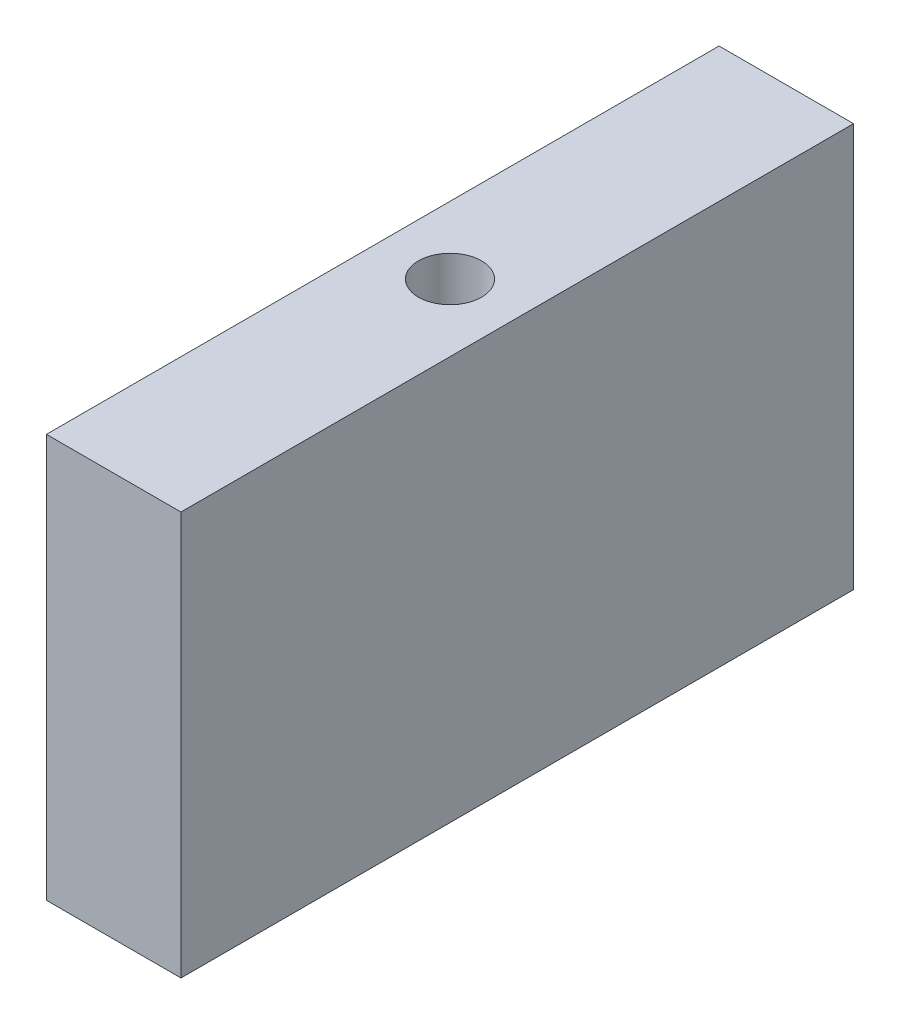
SolidWorks part; units mm, degrees
material "6061 Alloy"
ref_plane "Front Plane" through (0, 0, 0) normal (0, 0, 1) x (1, 0, 0)
ref_plane "Top Plane" through (0, 0, 0) normal (0, 1, 0) x (1, 0, 0)
ref_plane "Right Plane" through (0, 0, 0) normal (1, 0, 0) x (0, 0, -1)
sketch "Sketch1" plane through (0, 0, 0) normal (0, 1, 0) x (1, 0, 0)
  line L1 (-1.27, -6.35) -> (1.27, -6.35)
  line L2 (-1.27, -6.35) -> (-1.27, 6.35)
  line L3 (-1.27, 6.35) -> (1.27, 6.35)
  line L4 (1.27, -6.35) -> (1.27, 6.35)
  line L5 (-1.27, -6.35) -> (1.27, 6.35) construction
  line L6 (-1.27, 6.35) -> (1.27, -6.35) construction
  point P0 (0, 0)
  dimension "D1" = 2.54
  dimension "D2" = 12.7
extrude "Boss-Extrude1" add sketch "Sketch1" along normal blind 7.62
hole_wizard "#0-80 Tapped Hole1" positions "Sketch2" profile "Sketch3" tap size "#0-80" standard "ANSI Inch" end condition through all
sketch "Sketch2" plane through (0, 7.62, 0) normal (0, 1, 0) x (1, 0, 0)
  point P0 (0, 0)
sketch "Sketch3" plane through (0, 7.62, 0) normal (1, 0, 0) x (0, 0, 1)
  line L0 (0, 0) -> (0, 7.62)
  line L1 (0, 7.62) -> (0.5956, 7.62)
  line L2 (0.5956, 7.62) -> (0.5956, 0)
  line L5 (0.5956, 0) -> (0, 0)
  line L11 (0, -6.35) -> (0, 107.95) construction
  dimension "Thru Tap Drill Dia." = 1.1913
  dimension "Thru Tap Drill Depth" = 7.62
cosmetic thread "Hole Thread1" parameters "D2"=1.524
